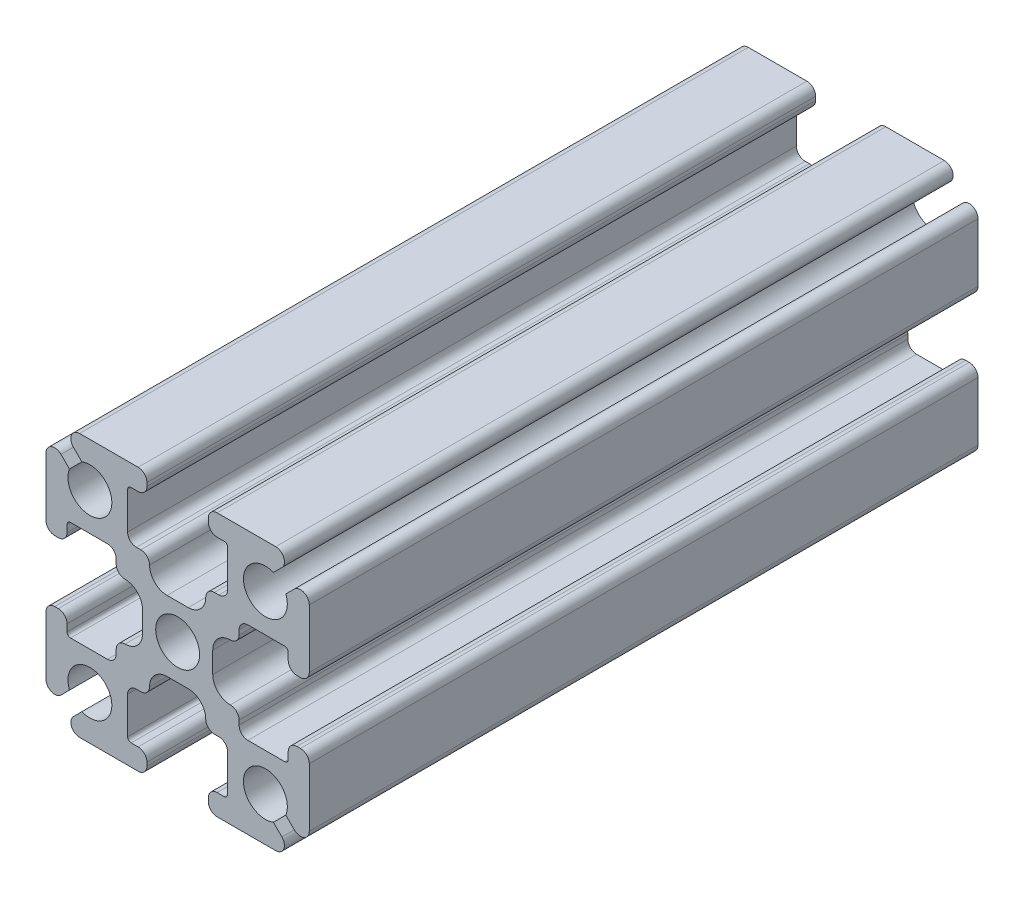
SolidWorks part; units mm, degrees
ref_plane "Front" through (0, 0, 0) normal (0, 0, 1) x (1, 0, 0)
ref_plane "Top" through (0, 0, 0) normal (0, 1, 0) x (1, 0, 0)
ref_plane "Right" through (0, 0, 0) normal (1, 0, 0) x (0, 0, -1)
sketch "Sketch1" plane through (0, 0, 0) normal (0, 0, 1) x (1, 0, 0)
  line L0 (6.6464, 5.9393) -> (6.1636, 5.4565)
  line L1 (5.4565, 6.1636) -> (5.9393, 6.6464)
  line L2 (5.5858, 7.5) -> (2.25, 7.5)
  line L3 (1.75, 7) -> (1.75, 6.8)
  line L4 (2.25, 6.3) -> (2.65, 6.3)
  line L5 (2.85, 6.1) -> (2.85, 4)
  line L6 (2.35, 3.5) -> (2.1, 3.5)
  line L7 (0.6, 2) -> (-0.6, 2)
  line L8 (-2.1, 3.5) -> (-2.35, 3.5)
  line L9 (-2.85, 4) -> (-2.85, 6.1)
  line L10 (-2.65, 6.3) -> (-2.25, 6.3)
  line L11 (-1.75, 6.8) -> (-1.75, 7)
  line L12 (-2.25, 7.5) -> (-5.5858, 7.5)
  line L13 (-5.9393, 6.6464) -> (-5.4565, 6.1636)
  line L14 (-6.1636, 5.4565) -> (-6.6464, 5.9393)
  line L15 (-7.5, 5.5858) -> (-7.5, 2.25)
  line L16 (-7, 1.75) -> (-6.8, 1.75)
  line L17 (-6.3, 2.25) -> (-6.3, 2.65)
  line L18 (-6.1, 2.85) -> (-4, 2.85)
  line L19 (-3.5, 2.35) -> (-3.5, 2.1)
  line L20 (-2, 0.6) -> (-2, -0.6)
  line L21 (-3.5, -2.1) -> (-3.5, -2.35)
  line L22 (-4, -2.85) -> (-6.1, -2.85)
  line L23 (-6.3, -2.65) -> (-6.3, -2.25)
  line L24 (-6.8, -1.75) -> (-7, -1.75)
  line L25 (-7.5, -2.25) -> (-7.5, -5.5858)
  line L26 (-6.6464, -5.9393) -> (-6.1636, -5.4565)
  line L27 (-5.4565, -6.1636) -> (-5.9393, -6.6464)
  line L28 (-5.5858, -7.5) -> (-2.25, -7.5)
  line L29 (-1.75, -7) -> (-1.75, -6.8)
  line L30 (-2.25, -6.3) -> (-2.65, -6.3)
  line L31 (-2.85, -6.1) -> (-2.85, -4)
  line L32 (-2.35, -3.5) -> (-2.1, -3.5)
  line L33 (-0.6, -2) -> (0.6, -2)
  line L34 (2.1, -3.5) -> (2.35, -3.5)
  line L35 (2.85, -4) -> (2.85, -6.1)
  line L36 (2.65, -6.3) -> (2.25, -6.3)
  line L37 (1.75, -6.8) -> (1.75, -7)
  line L38 (2.25, -7.5) -> (5.5858, -7.5)
  line L39 (5.9393, -6.6464) -> (5.4565, -6.1636)
  line L40 (6.1636, -5.4565) -> (6.6464, -5.9393)
  line L41 (7.5, -5.5858) -> (7.5, -2.25)
  line L42 (7, -1.75) -> (6.8, -1.75)
  line L43 (6.3, -2.25) -> (6.3, -2.65)
  line L44 (6.1, -2.85) -> (4, -2.85)
  line L45 (3.5, -2.35) -> (3.5, -2.1)
  line L46 (2, -0.6) -> (2, 0.6)
  line L47 (3.5, 2.1) -> (3.5, 2.35)
  line L48 (4, 2.85) -> (6.1, 2.85)
  line L49 (6.3, 2.65) -> (6.3, 2.25)
  line L50 (6.8, 1.75) -> (7, 1.75)
  line L51 (7.5, 2.25) -> (7.5, 5.5858)
  circle A0 centre (0, 0) radius 1.25
  arc A1 (6.1636, 5.4565) -> (5.4565, 6.1636) centre (5, 5) cw
  arc A2 (5.9393, 6.6464) -> (5.5858, 7.5) centre (5.5858, 7) ccw
  arc A3 (2.25, 7.5) -> (1.75, 7) centre (2.25, 7) ccw
  arc A4 (1.75, 6.8) -> (2.25, 6.3) centre (2.25, 6.8) ccw
  arc A5 (2.65, 6.3) -> (2.85, 6.1) centre (2.65, 6.1) cw
  arc A6 (2.85, 4) -> (2.35, 3.5) centre (2.35, 4) cw
  arc A7 (2.1, 3.5) -> (1.6, 3) centre (2.1, 3) ccw
  arc A8 (1.6, 3) -> (0.6, 2) centre (0.6, 3) cw
  arc A9 (-0.6, 2) -> (-1.6, 3) centre (-0.6, 3) cw
  arc A10 (-1.6, 3) -> (-2.1, 3.5) centre (-2.1, 3) ccw
  arc A11 (-2.35, 3.5) -> (-2.85, 4) centre (-2.35, 4) cw
  arc A12 (-2.85, 6.1) -> (-2.65, 6.3) centre (-2.65, 6.1) cw
  arc A13 (-2.25, 6.3) -> (-1.75, 6.8) centre (-2.25, 6.8) ccw
  arc A14 (-1.75, 7) -> (-2.25, 7.5) centre (-2.25, 7) ccw
  arc A15 (-5.5858, 7.5) -> (-5.9393, 6.6464) centre (-5.5858, 7) ccw
  arc A16 (-5.4565, 6.1636) -> (-6.1636, 5.4565) centre (-5, 5) cw
  arc A17 (-6.6464, 5.9393) -> (-7.5, 5.5858) centre (-7, 5.5858) ccw
  arc A18 (-7.5, 2.25) -> (-7, 1.75) centre (-7, 2.25) ccw
  arc A19 (-6.8, 1.75) -> (-6.3, 2.25) centre (-6.8, 2.25) ccw
  arc A20 (-6.3, 2.65) -> (-6.1, 2.85) centre (-6.1, 2.65) cw
  arc A21 (-4, 2.85) -> (-3.5, 2.35) centre (-4, 2.35) cw
  arc A22 (-3.5, 2.1) -> (-3, 1.6) centre (-3, 2.1) ccw
  arc A23 (-3, 1.6) -> (-2, 0.6) centre (-3, 0.6) cw
  arc A24 (-2, -0.6) -> (-3, -1.6) centre (-3, -0.6) cw
  arc A25 (-3, -1.6) -> (-3.5, -2.1) centre (-3, -2.1) ccw
  arc A26 (-3.5, -2.35) -> (-4, -2.85) centre (-4, -2.35) cw
  arc A27 (-6.1, -2.85) -> (-6.3, -2.65) centre (-6.1, -2.65) cw
  arc A28 (-6.3, -2.25) -> (-6.8, -1.75) centre (-6.8, -2.25) ccw
  arc A29 (-7, -1.75) -> (-7.5, -2.25) centre (-7, -2.25) ccw
  arc A30 (-7.5, -5.5858) -> (-6.6464, -5.9393) centre (-7, -5.5858) ccw
  arc A31 (-6.1636, -5.4565) -> (-5.4565, -6.1636) centre (-5, -5) cw
  arc A32 (-5.9393, -6.6464) -> (-5.5858, -7.5) centre (-5.5858, -7) ccw
  arc A33 (-2.25, -7.5) -> (-1.75, -7) centre (-2.25, -7) ccw
  arc A34 (-1.75, -6.8) -> (-2.25, -6.3) centre (-2.25, -6.8) ccw
  arc A35 (-2.65, -6.3) -> (-2.85, -6.1) centre (-2.65, -6.1) cw
  arc A36 (-2.85, -4) -> (-2.35, -3.5) centre (-2.35, -4) cw
  arc A37 (-2.1, -3.5) -> (-1.6, -3) centre (-2.1, -3) ccw
  arc A38 (-1.6, -3) -> (-0.6, -2) centre (-0.6, -3) cw
  arc A39 (0.6, -2) -> (1.6, -3) centre (0.6, -3) cw
  arc A40 (1.6, -3) -> (2.1, -3.5) centre (2.1, -3) ccw
  arc A41 (2.35, -3.5) -> (2.85, -4) centre (2.35, -4) cw
  arc A42 (2.85, -6.1) -> (2.65, -6.3) centre (2.65, -6.1) cw
  arc A43 (2.25, -6.3) -> (1.75, -6.8) centre (2.25, -6.8) ccw
  arc A44 (1.75, -7) -> (2.25, -7.5) centre (2.25, -7) ccw
  arc A45 (5.5858, -7.5) -> (5.9393, -6.6464) centre (5.5858, -7) ccw
  arc A46 (5.4565, -6.1636) -> (6.1636, -5.4565) centre (5, -5) cw
  arc A47 (6.6464, -5.9393) -> (7.5, -5.5858) centre (7, -5.5858) ccw
  arc A48 (7.5, -2.25) -> (7, -1.75) centre (7, -2.25) ccw
  arc A49 (6.8, -1.75) -> (6.3, -2.25) centre (6.8, -2.25) ccw
  arc A50 (6.3, -2.65) -> (6.1, -2.85) centre (6.1, -2.65) cw
  arc A51 (4, -2.85) -> (3.5, -2.35) centre (4, -2.35) cw
  arc A52 (3.5, -2.1) -> (3, -1.6) centre (3, -2.1) ccw
  arc A53 (3, -1.6) -> (2, -0.6) centre (3, -0.6) cw
  arc A54 (2, 0.6) -> (3, 1.6) centre (3, 0.6) cw
  arc A55 (3, 1.6) -> (3.5, 2.1) centre (3, 2.1) ccw
  arc A56 (3.5, 2.35) -> (4, 2.85) centre (4, 2.35) cw
  arc A57 (6.1, 2.85) -> (6.3, 2.65) centre (6.1, 2.65) cw
  arc A58 (6.3, 2.25) -> (6.8, 1.75) centre (6.8, 2.25) ccw
  arc A59 (7, 1.75) -> (7.5, 2.25) centre (7, 2.25) ccw
  arc A60 (7.5, 5.5858) -> (6.6464, 5.9393) centre (7, 5.5858) ccw
extrude "Boss-Extrude1" add sketch "Sketch1" along normal blind 38.1
